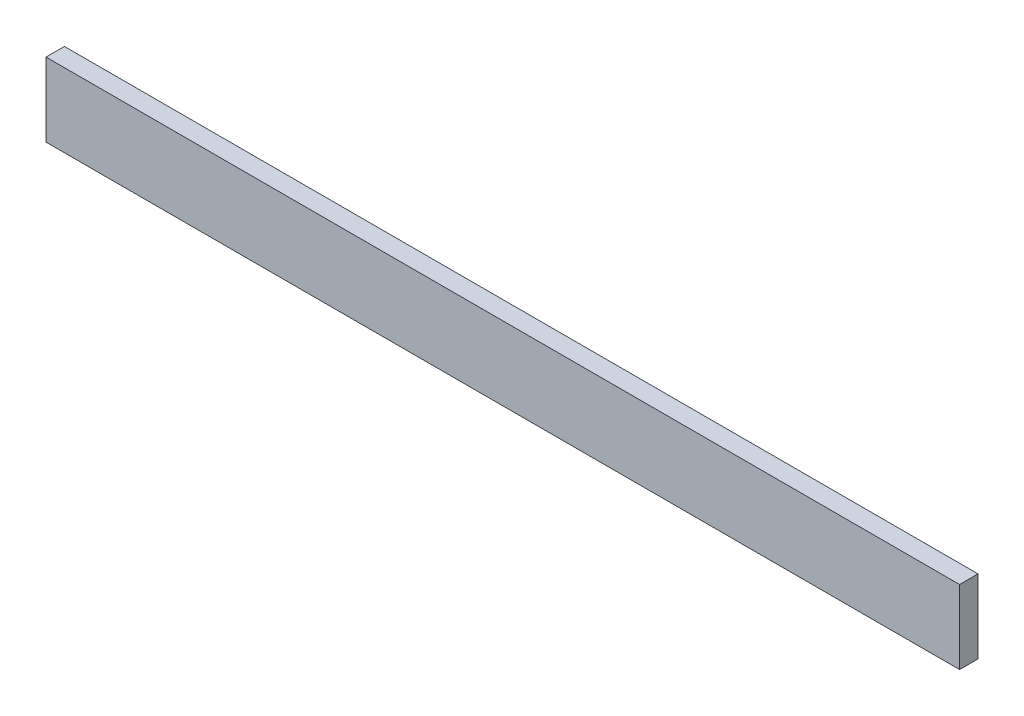
SolidWorks part; units mm, degrees
material "Spruce"
ref_plane "Front Plane" through (0, 0, 0) normal (0, 0, 1) x (1, 0, 0)
ref_plane "Top Plane" through (0, 0, 0) normal (0, 1, 0) x (1, 0, 0)
ref_plane "Right Plane" through (0, 0, 0) normal (1, 0, 0) x (0, 0, -1)
sketch "Sketch2" plane through (0, 0, -0.0008) normal (0, 0, 1) x (1, 0, 0)
  line L0 (-295.4563, 0.7927) -> (-295.4563, -5.5573)
  line L1 (-295.4563, -5.5573) -> (-216.7152, -5.5571)
  line L2 (-216.7152, -5.5571) -> (-216.7152, 0.7929)
  line L3 (-216.7152, 0.7929) -> (-295.4563, 0.7927)
extrude "Boss-Extrude1" add sketch "Sketch2" along normal blind 1.5875
